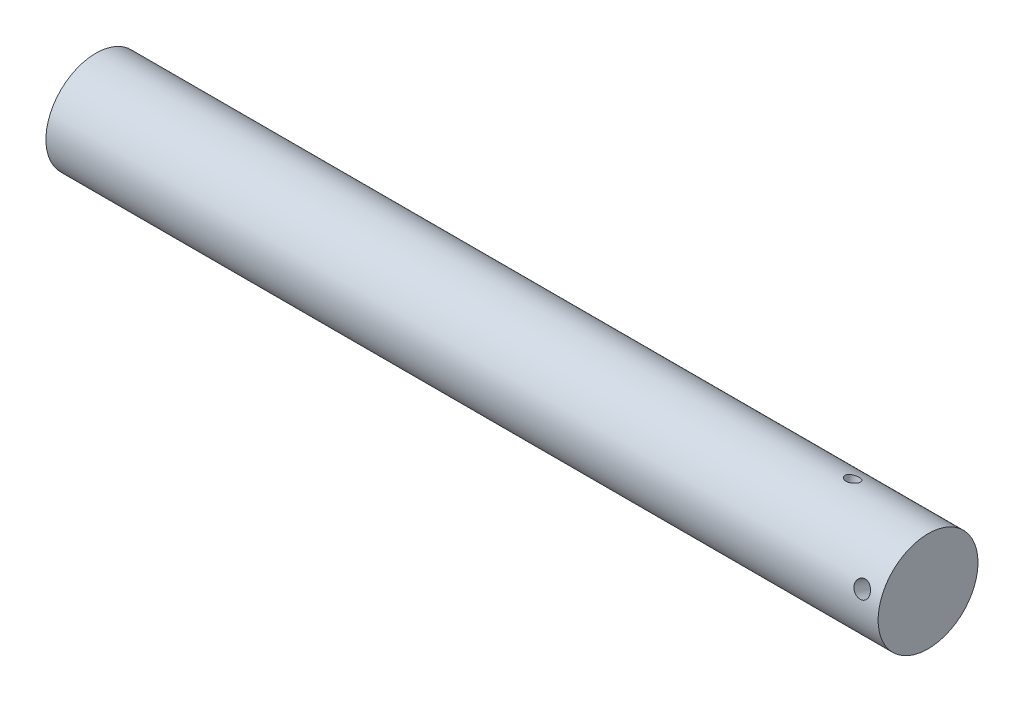
SolidWorks part; units mm, degrees
ref_plane "Front Plane" through (0, 0, 0) normal (0, 0, 1) x (1, 0, 0)
ref_plane "Top Plane" through (0, 0, 0) normal (0, 1, 0) x (1, 0, 0)
ref_plane "Right Plane" through (0, 0, 0) normal (1, 0, 0) x (0, 0, -1)
sketch "Sketch1" plane through (0, 0, 0) normal (1, 0, 0) x (0, 0, -1)
  circle A0 centre (0, 0) radius 7.5
extrude "Boss-Extrude1" add sketch "Sketch1" along normal blind 125
hole_wizard "3/32 (0.09375) Diameter Hole1" positions "3DSketch1" profile "Sketch2" hole size "3/32" standard "ANSI Inch" end condition through all
sketch3d "3DSketch1"
  point P0 (122.1971, -2.4169, -7.0999)
sketch "Sketch2" plane through (122.1971, -2.4169, -7.0999) normal (1, 0, 0) x (0, 0.9467, -0.3223)
  line L0 (0, 0) -> (0, 17.0168)
  line L1 (0, 17.0168) -> (1.1906, 17.0168)
  line L2 (1.1906, 17.0168) -> (1.1906, 0)
  line L5 (1.1906, 0) -> (0, 0)
  line L11 (0, -6.35) -> (0, 107.95) construction
  dimension "Thru Hole Dia." = 2.3812
  dimension "Thru Hole Depth" = 17.0168
hole_wizard "2mm Diameter Hole" positions "3DSketch2" profile "Sketch3" hole size "3/32" standard "ANSI Inch" end condition through all
sketch3d "3DSketch2"
  circle A0 centre (125, 0, 0) radius 7.5 construction
  point P0 (112.0096, 7.3128, -1.6651)
  point P5 (132.5, 0, 0)
  dimension "D1" = 15
sketch "Sketch3" plane through (112.0096, 7.3128, -1.6651) normal (1, 0, 0) x (0, 0.222, 0.975)
  line L0 (0, 0) -> (0, 16.4779)
  line L1 (0, 16.4779) -> (1, 16.4779)
  line L2 (1, 16.4779) -> (1, 0)
  line L5 (1, 0) -> (0, 0)
  line L11 (0, -6.35) -> (0, 107.95) construction
  dimension "Thru Hole Dia." = 2
  dimension "Thru Hole Depth" = 16.4779
